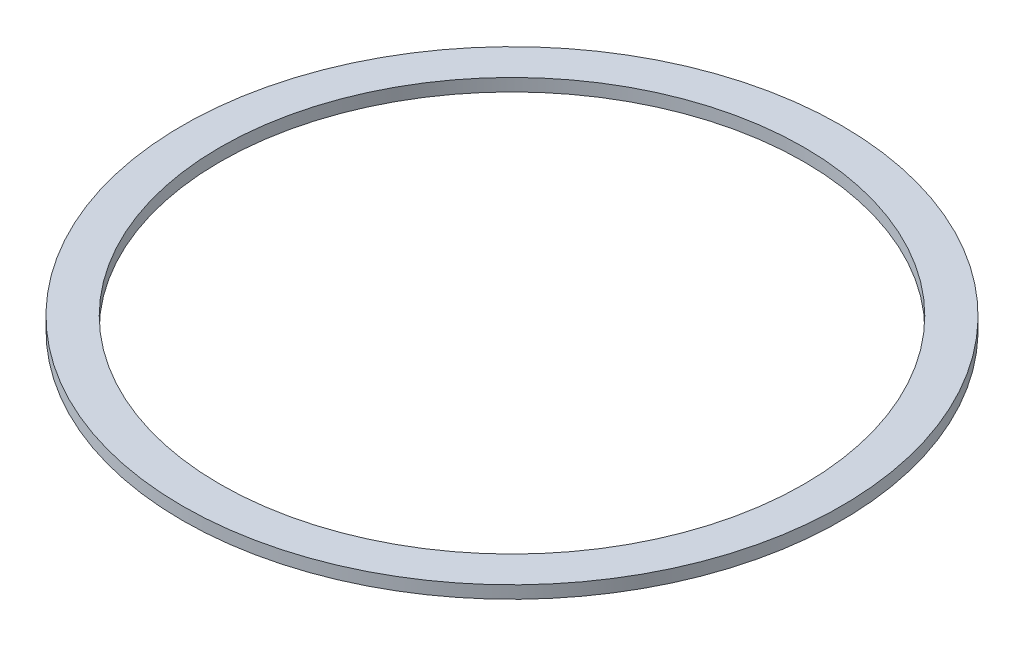
SolidWorks part; units mm, degrees
ref_plane "Front Plane" through (0, 0, 0) normal (0, 0, 1) x (1, 0, 0)
ref_plane "Top Plane" through (0, 0, 0) normal (0, 1, 0) x (1, 0, 0)
ref_plane "Right Plane" through (0, 0, 0) normal (1, 0, 0) x (0, 0, -1)
sketch "Sketch1" plane through (0, 0, 0) normal (0, 1, 0) x (1, 0, 0)
  circle A0 centre (0, 0) radius 52.5
  circle A1 centre (0, 0) radius 46.5
  dimension "D1" = 105
  dimension "D2" = 93
extrude "Boss-Extrude1" add sketch "Sketch1" along normal blind 2
